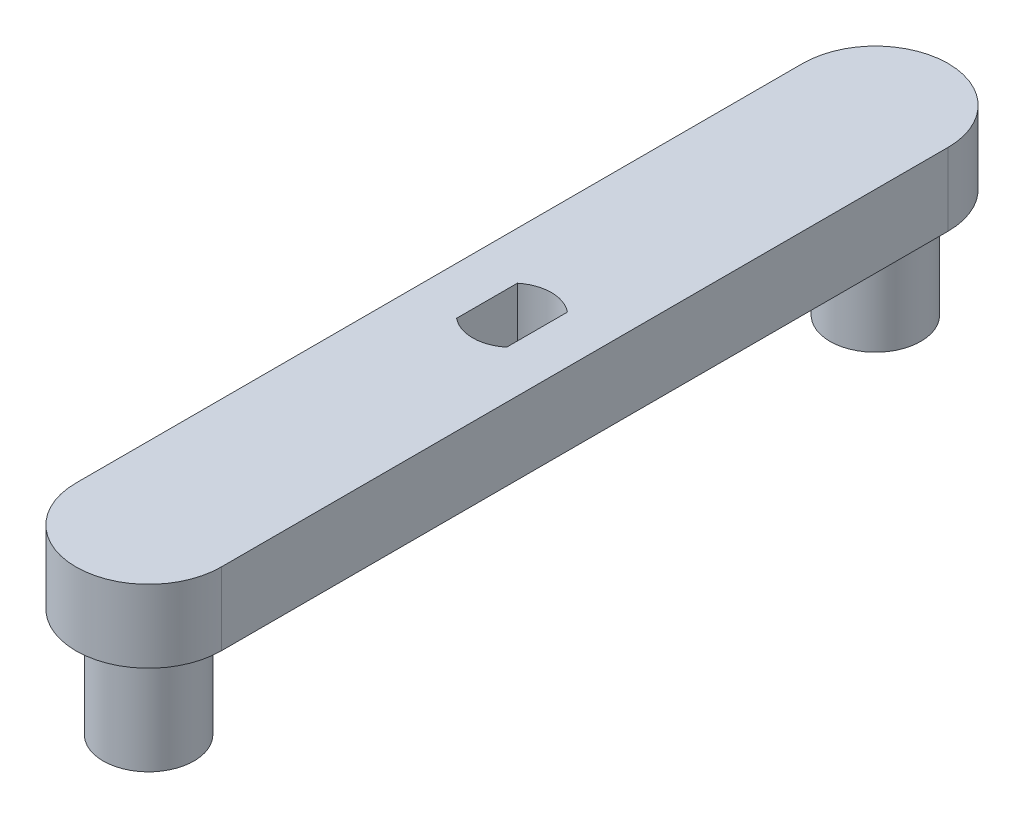
SolidWorks part; units mm, degrees
ref_plane "Front Plane" through (0, 0, 0) normal (0, 0, 1) x (1, 0, 0)
ref_plane "Top Plane" through (0, 0, 0) normal (0, 1, 0) x (1, 0, 0)
ref_plane "Right Plane" through (0, 0, 0) normal (1, 0, 0) x (0, 0, -1)
sketch "Sketch1" plane through (0, 0, 0) normal (0, 1, 0) x (1, 0, 0)
  line L0 (0, 0) -> (0, 25.4)
  line L1 (0, 0) -> (0, -25.4)
  line L4 (-5.08, 25.4) -> (-5.08, -25.4)
  line L5 (5.08, -25.4) -> (5.08, 25.4)
  arc A0 (5.08, 25.4) -> (-5.08, 25.4) centre (0, 25.4) ccw
  arc A1 (-5.08, -25.4) -> (5.08, -25.4) centre (0, -25.4) ccw
sketch "Sketch2" plane through (0, 0, 0) normal (0, 1, 0) x (1, 0, 0)
  line L0 (-5.08, 25.4) -> (-5.08, -25.4)
  line L1 (5.08, -25.4) -> (5.08, 25.4)
  arc A0 (5.08, 25.4) -> (-5.08, 25.4) centre (0, 25.4) ccw
  arc A1 (-5.08, -25.4) -> (5.08, -25.4) centre (0, -25.4) ccw
extrude "Boss-Extrude1" add sketch "Sketch2" along normal blind 5.08
sketch "Sketch3" plane through (0, 0, 0) normal (0, -1, 0) x (-1, 0, 0)
  circle A0 centre (0, -25.4) radius 3.175
  circle A1 centre (0, 25.4) radius 3.175
extrude "Boss-Extrude2" add sketch "Sketch3" along normal blind 7.62
sketch "Sketch5" plane through (0, -7.62, 0) normal (0, -1, 0) x (1, 0, 0)
  circle A0 centre (0, 25.4) radius 5.08
sketch "Sketch6" plane through (0, -7.62, 0) normal (0, -1, 0) x (1, 0, 0)
  circle A0 centre (0, 25.4) radius 5.08
sketch "Sketch7" plane through (0, -7.62, 0) normal (0, -1, 0) x (1, 0, 0)
  circle A0 centre (0, -25.4) radius 5.08
sketch "Sketch8" plane through (0, -7.62, 0) normal (0, -1, 0) x (1, 0, 0)
  circle A0 centre (0, -25.4) radius 5.08
sketch "Sketch9" plane through (0, 5.08, 0) normal (0, 1, 0) x (1, 0, 0)
  line L0 (0, 0) -> (-1.75, 0)
  line L1 (-1.75, 0) -> (0, 0)
  line L2 (0, 0) -> (1.75, 0)
  line L3 (-1.75, 0) -> (-1.75, 2.1213)
  line L4 (-1.75, 2.1213) -> (-1.75, -2.1213)
  line L5 (1.75, 0) -> (1.75, 2.1213)
  line L6 (1.75, 2.1213) -> (1.75, -2.1213)
  arc A0 (1.75, 2.1213) -> (-1.75, 2.1213) centre (0, 0) ccw
  arc A1 (-1.75, -2.1213) -> (1.75, -2.1213) centre (0, 0) ccw
sketch "Sketch10" plane through (0, 5.08, 0) normal (0, 1, 0) x (1, 0, 0)
  line L0 (-1.75, 2.1213) -> (-1.75, -2.1213)
  line L1 (1.75, 2.1213) -> (1.75, -2.1213)
  arc A0 (1.75, 2.1213) -> (-1.75, 2.1213) centre (0, 0) ccw
  arc A1 (-1.75, -2.1213) -> (1.75, -2.1213) centre (0, 0) ccw
extrude "Cut-Extrude1" cut sketch "Sketch10" against normal up to next
